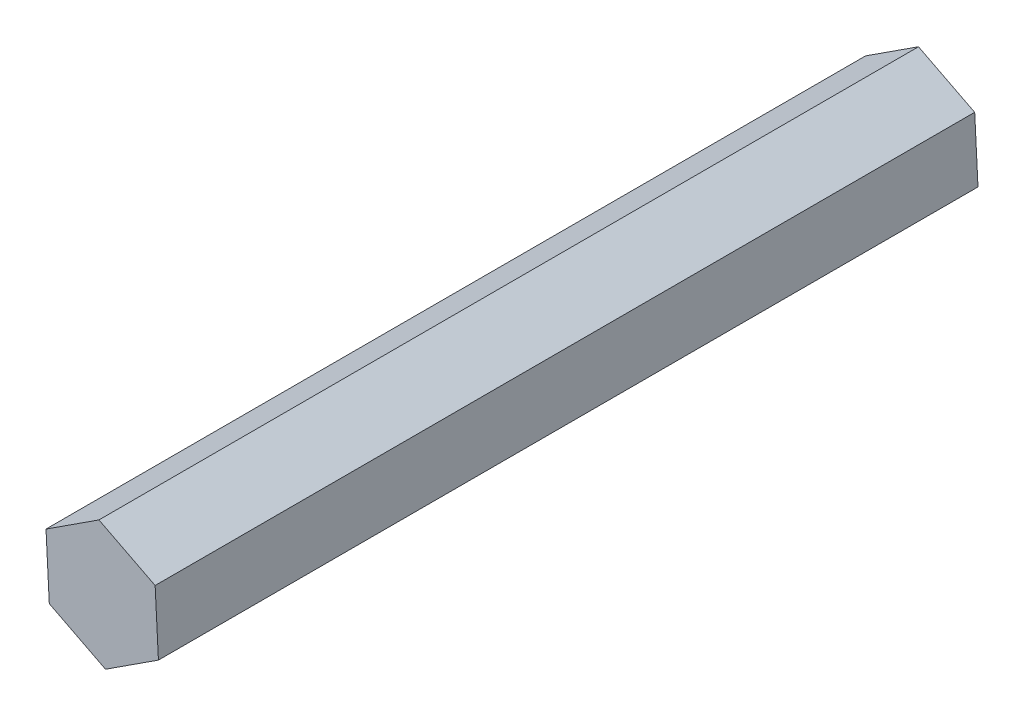
SolidWorks part; units mm, degrees
ref_plane "Front Plane" through (0, 0, 0) normal (0, 0, 1) x (1, 0, 0)
ref_plane "Top Plane" through (0, 0, 0) normal (0, 1, 0) x (1, 0, 0)
ref_plane "Right Plane" through (0, 0, 0) normal (1, 0, 0) x (0, 0, -1)
sketch "Sketch2" plane through (0, 0, 0) normal (0, 0, 1) x (1, 0, 0)
  line L1 (-6.5329, 3.3293) -> (-6.1497, -3.993)
  line L2 (-6.1497, -3.993) -> (0.3832, -7.3223)
  line L3 (0.3832, -7.3223) -> (6.5329, -3.3293)
  line L4 (6.5329, -3.3293) -> (6.1497, 3.993)
  line L5 (6.1497, 3.993) -> (-0.3832, 7.3223)
  line L6 (-0.3832, 7.3223) -> (-6.5329, 3.3293)
  circle A0 centre (0, 0) radius 6.35 construction
  point P1 (6.3413, 0.3319)
  dimension "D1" = 12.7
extrude "Boss-Extrude2" add sketch "Sketch2" along normal blind 95.25
sketch "Sketch3" plane through (0, 0, 95.25) normal (0, 0, 1) x (1, 0, 0)
  circle A0 centre (0, 0) radius 6.35
  dimension "D1" = 12.7
equation "\"4n\"=3.75"
